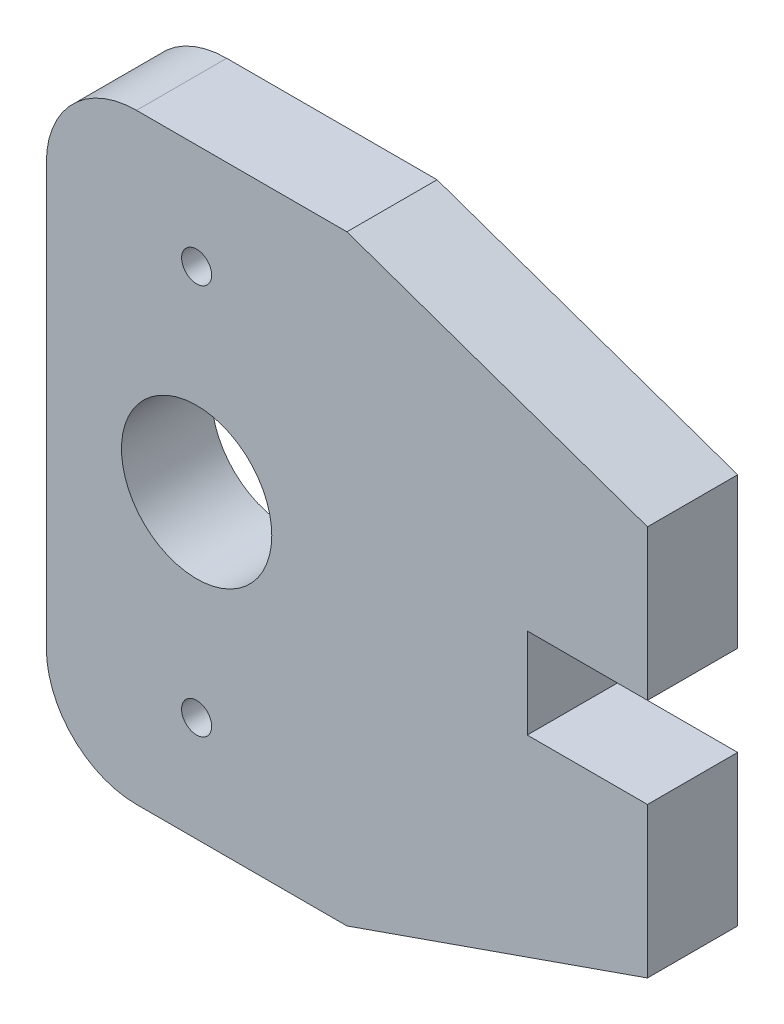
SolidWorks part; units mm, degrees
ref_plane "Front Plane" through (0, 0, 0) normal (0, 0, 1) x (1, 0, 0)
ref_plane "Top Plane" through (0, 0, 0) normal (0, 1, 0) x (1, 0, 0)
ref_plane "Right Plane" through (0, 0, 0) normal (1, 0, 0) x (0, 0, -1)
sketch "Sketch1" plane through (0, 0, 0) normal (0, 0, 1) x (1, 0, 0)
  line L0 (-5, 14.0302) -> (-5, -15.297) construction
  line L1 (-10, 10) -> (0, 10)
  line L2 (-10, 10) -> (-10, -10)
  line L3 (-10, -10) -> (0, -10)
  line L4 (10, 6.5) -> (10, 1.5)
  line L5 (-10, 10) -> (10, -10) construction
  line L6 (-10, -10) -> (10, 10) construction
  line L7 (-11.5643, 0) -> (7.2451, 0) construction
  line L8 (0, 10) -> (10, 6.5)
  line L9 (6, -1.5) -> (10, -1.5)
  line L10 (6, -1.5) -> (6, 1.5)
  line L11 (6, 1.5) -> (10, 1.5)
  line L12 (10, -1.5) -> (10, -6.5)
  line L13 (6, -1.5) -> (14, 1.5) construction
  line L14 (6, 1.5) -> (14, -1.5) construction
  line L15 (0, -10) -> (10, -6.5)
  circle A0 centre (-5, 6.5) radius 0.5
  circle A1 centre (-5, -6.5) radius 0.5
  point P0 (0, 0)
  point P14 (10, 0)
  dimension "D4" = 1
  dimension "D6" = 8
  dimension "D1" = 20
  dimension "D2" = 20
  dimension "D3" = 5
  dimension "D5" = 13
  dimension "D7" = 3
extrude "Boss-Extrude1" add sketch "Sketch1" along normal blind 3
fillet "Fillet1" radius 3 2 edges at (-10, -10, 1.5) (-10, 10, 1.5)
sketch "Sketch2" plane through (0, 0, 3) normal (0, 0, 1) x (1, 0, 0)
  line L0 (-7.6923, 0) -> (3.5182, 0) construction
  circle A0 centre (-5, 0) radius 2.5
  dimension "D1" = 5
extrude "Cut-Extrude1" cut sketch "Sketch2" against normal blind 3
